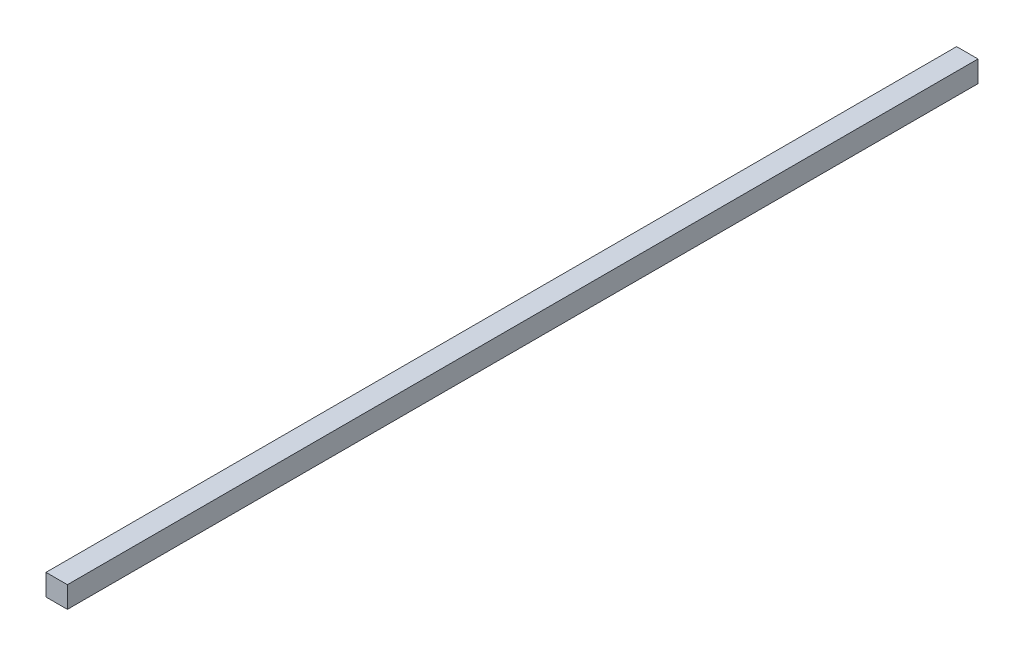
SolidWorks part; units mm, degrees
material "6061-T6 (SS)"
ref_plane "Front Plane" through (0, 0, 0) normal (0, 0, 1) x (1, 0, 0)
ref_plane "Top Plane" through (0, 0, 0) normal (0, 1, 0) x (1, 0, 0)
ref_plane "Right Plane" through (0, 0, 0) normal (1, 0, 0) x (0, 0, -1)
sketch "Sketch1" plane through (0, 0, 0) normal (0, 0, 1) x (1, 0, 0)
  line L1 (-3, -3) -> (3, -3)
  line L2 (-3, -3) -> (-3, 3)
  line L3 (-3, 3) -> (3, 3)
  line L4 (3, -3) -> (3, 3)
  line L5 (-3, -3) -> (3, 3) construction
  line L6 (-3, 3) -> (3, -3) construction
  point P0 (0, 0)
  dimension "D1" = 6
  dimension "D2" = 6
extrude "Boss-Extrude1" add sketch "Sketch1" along normal blind 255.31
equation "\"Length of Bar\"= ( 0.2286 * 36.00 * 69000 ) / 2224.11"
